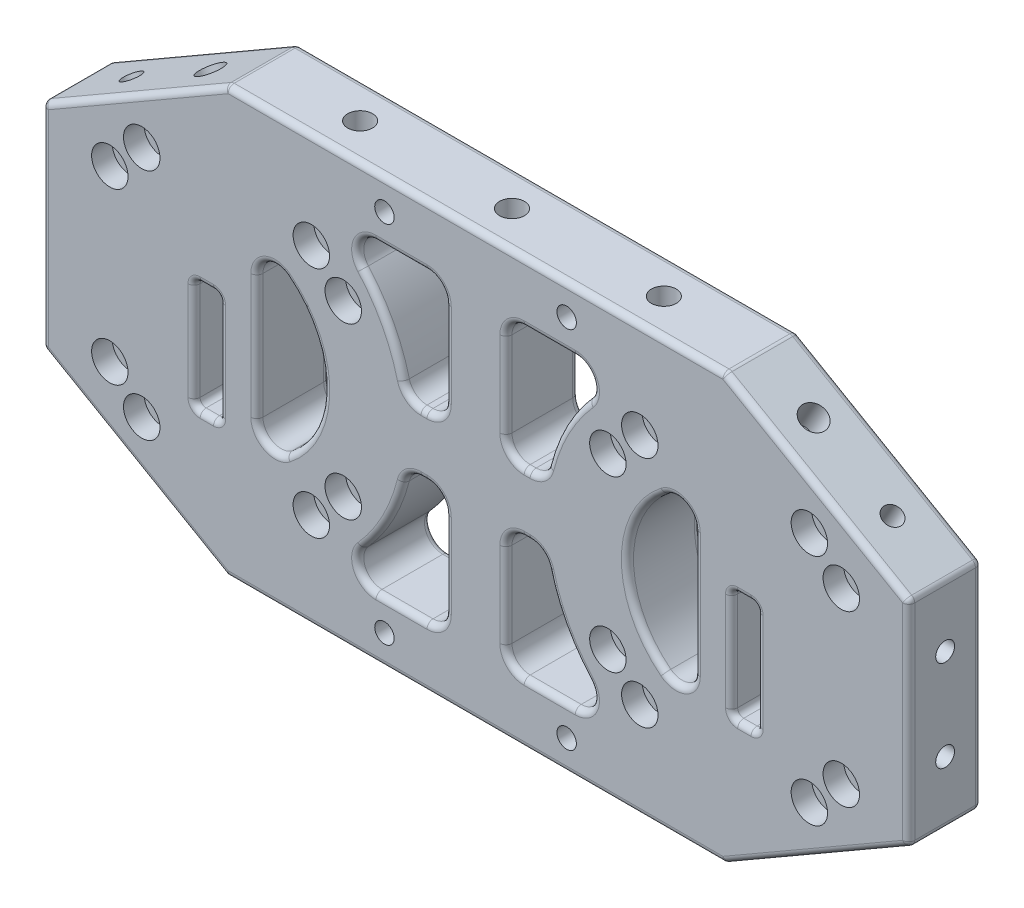
SolidWorks part; units mm, degrees
material "ABS"
ref_plane "前视基准面" through (0, 0, 0) normal (0, 0, 1) x (1, 0, 0)
ref_plane "上视基准面" through (0, 0, 0) normal (0, 1, 0) x (1, 0, 0)
ref_plane "右视基准面" through (0, 0, 0) normal (1, 0, 0) x (0, 0, -1)
other "Configuration Table"
sketch "草图1" plane through (0, 0, 0) normal (0, 0, 1) x (1, 0, 0)
  line L0 (0, 0) -> (41, 0)
  line L1 (0, 0) -> (41, 0) construction
  line L2 (0, 0) -> (0, 70) construction
  line L3 (0, 70) -> (41, 70) construction
  line L4 (41, 0) -> (41, 70) construction
  line L5 (0, 70) -> (41, 70)
  line L6 (-30.3109, 35) -> (41, 35) construction
  line L7 (0, 35) -> (-19.2142, 21.0401) construction
  line L8 (0, 35) -> (-13.9599, 15.7858) construction
  line L9 (41, 70) -> (41, 0)
  line L10 (0, 70) -> (-30.3109, 52.5)
  line L11 (0, 70) -> (-30.3109, 52.5) construction
  line L12 (-30.3109, 52.5) -> (-30.3109, 17.5) construction
  line L13 (-30.3109, 17.5) -> (0, 0) construction
  line L14 (36, 40) -> (36, 60)
  line L20 (36, 60) -> (16.5831, 60)
  line L21 (36, 40) -> (29.5804, 40)
  line L22 (36, 30) -> (36, 10)
  line L23 (36, 10) -> (16.5831, 10)
  line L24 (36, 30) -> (29.5804, 30)
  line L25 (0, 0) -> (30.3109, 17.5) construction
  line L26 (30.3109, 17.5) -> (30.3109, 52.5) construction
  line L27 (30.3109, 52.5) -> (0, 70) construction
  line L28 (-30.3109, 52.5) -> (-30.3109, 17.5)
  line L29 (-30.3109, 17.5) -> (0, 0)
  line L30 (5, 50.1987) -> (5, 19.8013)
  line L31 (-5.35, 39.6) -> (-1.15, 39.6)
  line L32 (-5.35, 39.6) -> (-5.35, 21.4)
  line L33 (-5.35, 21.4) -> (-1.15, 21.4)
  line L34 (-1.15, 39.6) -> (-1.15, 21.4)
  circle A2 centre (0, 35) radius 16 construction
  circle A4 centre (0, 35) radius 23.75 construction
  circle A14 centre (0, 35) radius 30 construction
  arc A24 (16.5831, 60) -> (29.5804, 40) centre (0, 35) cw
  arc A25 (16.5831, 10) -> (29.5804, 30) centre (0, 35) ccw
  circle A26 centre (0, 35) radius 30.3109 construction
  arc A27 (5, 50.1987) -> (5, 19.8013) centre (0, 35) cw
  point P13 (-19.2142, 21.0401)
  point P14 (-13.9599, 15.7858)
  point P23 (-13.9599, 54.2142)
  point P24 (-19.2142, 48.9599)
  point P25 (19.2142, 48.9599)
  point P26 (13.9599, 54.2142)
  point P27 (13.9599, 15.7858)
  point P28 (19.2142, 21.0401)
  dimension "D3" = 32
  dimension "D4" = 60
  dimension "D5" = 21.4
  dimension "D6" = 47.5
  dimension "D7" = 36
  dimension "D8" = 36
  dimension "D12" = 18.2
  dimension "D18" = 5
  dimension "D1" = 70
  dimension "D2" = 41
  dimension "D9" = 4
  dimension "D13" = 42.15
  dimension "D14" = 46.35
  dimension "D17" = 5
  dimension "D19" = 10
  dimension "D15" = 5
extrude "凸台-拉伸1" add sketch "草图1" along normal blind 12
mirror "镜向2" about plane through (41, 70, 12) normal (-1, 0, 0) of "凸台-拉伸1"
fillet "圆角2" radius 3 20 edges at (36, 30, 6) (36, 10, 6) (16.5831, 10, 6) (29.5804, 30, 6) (65.4169, 10, 6) (52.4196, 30, 6) (46, 30, 6) (46, 10, 6) (46, 40, 6) (46, 60, 6) (65.4169, 60, 6) (52.4196, 40, 6) (29.5804, 40, 6) (16.5831, 60, 6) (36, 40, 6) (36, 60, 6) (77, 50.1987, 6) (77, 19.8013, 6) (5, 50.1987, 6) (5, 19.8013, 6)
sketch "草图2" plane through (-30.3109, 52.5, 0) normal (-0.5, 0.866, 0) x (0.866, 0.5, 0)
  line L0 (0, -6) -> (35, -6) construction
  line L1 (0, -12) -> (0, 0) construction
  line L2 (35, -12) -> (35, 0) construction
  circle A0 centre (10, -6) radius 1.55
  circle A1 centre (25, -6) radius 1.55
  dimension "D1" = 3.1
  dimension "D2" = 3.1
  dimension "D3" = 15
  dimension "D4" = 10
extrude "切除-拉伸1" cut sketch "草图2" against normal blind 5
sketch "草图3" plane through (50.8109, 88.007, 0) normal (0.5, 0.866, 0) x (0.866, -0.5, 0)
  line L0 (36.0141, -6) -> (71.0141, -6) construction
  line L1 (36.0141, -12) -> (36.0141, 0) construction
  line L2 (71.0141, -12) -> (71.0141, 0) construction
  circle A0 centre (61.0141, -6) radius 1.55
  circle A1 centre (46.0141, -6) radius 1.55
  dimension "D1" = 3.1
  dimension "D2" = 3.1
  dimension "D3" = 15
  dimension "D4" = 10
extrude "切除-拉伸2" cut sketch "草图3" against normal blind 5
sketch "草图4" plane through (0, 0, 0) normal (-0.5, -0.866, 0) x (0.866, -0.5, 0)
  line L0 (-35, 6) -> (0, 6) construction
  line L1 (-35, 12) -> (-35, 0) construction
  line L2 (0, 12) -> (0, 0) construction
  circle A0 centre (-10, 6) radius 1.55
  circle A1 centre (-25, 6) radius 1.55
  dimension "D3" = 3.1
  dimension "D4" = 3.1
  dimension "D1" = 15
  dimension "D2" = 10
extrude "切除-拉伸3" cut sketch "草图4" against normal blind 5
sketch "草图5" plane through (20.5, -35.507, 0) normal (0.5, -0.866, 0) x (0.866, 0.5, 0)
  line L0 (71.0141, 6) -> (106.0141, 6) construction
  line L1 (71.0141, 12) -> (71.0141, 0) construction
  line L2 (106.0141, 12) -> (106.0141, 0) construction
  circle A0 centre (81.0141, 6) radius 1.55
  circle A1 centre (96.0141, 6) radius 1.55
  dimension "D1" = 3.1
  dimension "D2" = 3.1
  dimension "D3" = 15
  dimension "D4" = 10
extrude "切除-拉伸4" cut sketch "草图5" against normal blind 5
sketch "草图6" plane through (112.3109, 0, 0) normal (1, 0, 0) x (0, 0, -1)
  line L0 (-6, 52.5) -> (-6, 17.5) construction
  line L1 (-12, 52.5) -> (0, 52.5) construction
  line L2 (-12, 17.5) -> (0, 17.5) construction
  circle A0 centre (-6, 42.5) radius 1.55
  circle A1 centre (-6, 27.5) radius 1.55
  dimension "D1" = 3.1
  dimension "D2" = 3.1
  dimension "D3" = 15
  dimension "D4" = 10
extrude "切除-拉伸5" cut sketch "草图6" against normal blind 5
sketch "草图7" plane through (0, 0, 0) normal (0, -1, 0) x (1, 0, 0)
  line L0 (0, 6) -> (82, 6) construction
  line L1 (0, 12) -> (0, 0) construction
  line L2 (82, 12) -> (82, 0) construction
  circle A0 centre (16, 6) radius 2.05
  circle A1 centre (41, 6) radius 2.05
  circle A2 centre (66, 6) radius 2.05
  dimension "D1" = 4.1
  dimension "D2" = 4.1
  dimension "D3" = 4.1
  dimension "D4" = 25
  dimension "D5" = 25
extrude "切除-拉伸6" cut sketch "草图7" against normal blind 5
sketch "草图8" plane through (0, 70, 0) normal (0, 1, 0) x (1, 0, 0)
  line L0 (0, -6) -> (82, -6) construction
  line L1 (0, -12) -> (0, 0) construction
  line L2 (82, -12) -> (82, 0) construction
  circle A0 centre (41, -6) radius 2.05
  circle A1 centre (66, -6) radius 2.05
  circle A2 centre (16, -6) radius 2.05
  dimension "D3" = 4.1
  dimension "D4" = 4.1
  dimension "D5" = 4.1
  dimension "D1" = 25
  dimension "D2" = 25
extrude "切除-拉伸7" cut sketch "草图8" against normal blind 5
sketch "草图9" plane through (-30.3109, 0, 0) normal (-1, 0, 0) x (0, 0, 1)
  line L0 (6, 52.5) -> (6, 17.5) construction
  line L1 (12, 52.5) -> (0, 52.5) construction
  line L2 (12, 17.5) -> (0, 17.5) construction
  circle A0 centre (6, 42.5) radius 1.55
  circle A1 centre (6, 27.5) radius 1.55
  dimension "D3" = 3.1
  dimension "D4" = 3.1
  dimension "D1" = 15
  dimension "D2" = 10
extrude "切除-拉伸8" cut sketch "草图9" against normal blind 5
sketch "草图10" plane through (-30.3109, 52.5, 0) normal (-0.5, 0.866, 0) x (0.866, 0.5, 0)
  circle A0 centre (25, -6) radius 2.05
  dimension "D1" = 4.1
extrude "切除-拉伸9" cut sketch "草图10" against normal blind 5
sketch "草图11" plane through (50.8109, 88.007, 0) normal (0.5, 0.866, 0) x (0.866, -0.5, 0)
  circle A0 centre (46.0141, -6) radius 2.05
  dimension "D1" = 4.1
extrude "切除-拉伸10" cut sketch "草图11" against normal blind 5
fillet "圆角3" radius 1 128 edges at (-3.25, 39.6, 12) (-3.25, 39.6, 0) (-3.25, 21.4, 12) (-3.25, 21.4, 0) (85.25, 39.6, 0) (85.25, 39.6, 12) (85.25, 21.4, 0) (85.25, 21.4, 12) (6.6844, 47.9431, 0) (16, 35, 0) (6.6844, 22.0569, 0) (6.6844, 47.9431, 12) (16, 35, 12) (6.6844, 22.0569, 12) (75.3156, 47.9431, 12) (66, 35, 12) (66, 35, 0) (75.3156, 22.0569, 12) (75.3156, 47.9431, 0) (75.3156, 22.0569, 0) (51.8308, 29.3645, 12) (49.4922, 30, 0) (49.4922, 30, 12) (46.8787, 29.1213, 12) (46, 20, 0) (46, 20, 12) (46.8787, 10.8787, 12) (53.2016, 10, 12) (53.2016, 10, 0) (60.1419, 11.7753, 12) (51.8308, 29.3645, 0) (46.8787, 29.1213, 0) (46.8787, 10.8787, 0) (60.1419, 11.7753, 0) (60.1419, 58.2247, 0) (53.2016, 60, 12) (53.2016, 60, 0) (46.8787, 59.1213, 0) (46, 50, 12) (46, 50, 0) (46.8787, 40.8787, 0) (49.4922, 40, 0) (49.4922, 40, 12) (51.8308, 40.6355, 0) (60.1419, 58.2247, 12) (46.8787, 59.1213, 12) (46.8787, 40.8787, 12) (51.8308, 40.6355, 12) (21.8581, 58.2247, 0) (28.7984, 60, 0) (35.1213, 59.1213, 0) (36, 50, 0) (35.1213, 40.8787, 0) (32.5078, 40, 0) (30.1692, 40.6355, 0) (21.8581, 58.2247, 12) (28.7984, 60, 12) (35.1213, 59.1213, 12) (36, 50, 12) (35.1213, 40.8787, 12) (32.5078, 40, 12) (30.1692, 40.6355, 12) (30.1692, 29.3645, 0) (32.5078, 30, 0) (35.1213, 29.1213, 0) (36, 20, 0) (35.1213, 10.8787, 0) (28.7984, 10, 0) (21.8581, 11.7753, 0) (30.1692, 29.3645, 12) (32.5078, 30, 12) (35.1213, 29.1213, 12) (36, 20, 12) (35.1213, 10.8787, 12) (28.7984, 10, 12) (21.8581, 11.7753, 12) (-5.35, 21.4, 6) (-5.35, 30.5, 12) (-5.35, 39.6, 6) (-5.35, 30.5, 0) (-1.15, 39.6, 6) (-1.15, 30.5, 12) (-1.15, 21.4, 6) (-1.15, 30.5, 0) (83.15, 21.4, 6) (83.15, 30.5, 0) (83.15, 30.5, 12) (83.15, 39.6, 6) (87.35, 39.6, 6) (87.35, 30.5, 0) (87.35, 30.5, 12) (87.35, 21.4, 6) (5, 35, 0) (5, 35, 12) (77, 35, 0) (77, 35, 12) (55.4919, 20.9529, 0) (55.4919, 20.9529, 12) (55.4919, 49.0471, 12) (55.4919, 49.0471, 0) (26.5081, 49.0471, 0) (26.5081, 49.0471, 12) (26.5081, 20.9529, 0) (26.5081, 20.9529, 12) (41, 70, 12) (97.1554, 61.25, 0) (97.1554, 61.25, 12) (112.3109, 35, 0) (112.3109, 35, 12) (97.1554, 8.75, 0) (97.1554, 8.75, 12) (41, 0, 12) (-15.1554, 8.75, 12) (-15.1554, 61.25, 12) (-30.3109, 35, 12) (-15.1554, 8.75, 0) (-30.3109, 35, 0) (-15.1554, 61.25, 0) (41, 70, 0) (41, 0, 0) (0, 70, 6) (-30.3109, 52.5, 6) (-30.3109, 17.5, 6) (0, 0, 6) (112.3109, 17.5, 6) (82, 0, 6) (112.3109, 52.5, 6) (82, 70, 6)
sketch "草图12" plane through (0, 0, 12) normal (0, 0, 1) x (1, 0, 0)
  line L0 (41, 70) -> (41, 0) construction
  line L1 (0.2679, 70) -> (81.7321, 70) construction
  line L2 (81.7321, 0) -> (0.2679, 0) construction
  line L3 (0, 35) -> (0, 11.25) construction
  line L4 (0, 35) -> (-23.75, 35) construction
  line L5 (-19.2142, 21.0401) -> (0, 35) construction
  line L6 (0, 35) -> (-13.9599, 15.7858) construction
  circle A0 centre (0, 35) radius 23.75 construction
  point P10 (-19.2142, 21.0401)
  point P13 (-13.9599, 15.7858)
  point P15 (62.7858, 21.0401)
  point P17 (68.0401, 15.7858)
  point P18 (95.9599, 15.7858)
  point P19 (-13.9599, 54.2142)
  point P20 (-19.2142, 48.9599)
  point P21 (19.2142, 48.9599)
  point P22 (13.9599, 54.2142)
  point P23 (13.9599, 15.7858)
  point P24 (19.2142, 21.0401)
  point P25 (101.2142, 21.0401)
  point P26 (101.2142, 48.9599)
  point P27 (95.9599, 54.2142)
  point P28 (68.0401, 54.2142)
  point P29 (62.7858, 48.9599)
  dimension "D1" = 47.5
  dimension "D2" = 36
  dimension "D3" = 36
  dimension "D4" = 4
hole_wizard "M3 六角圆柱头螺钉的柱形沉头孔1" positions "草图12" profile "草图13" counterbore size "M3" standard "GB" end condition through all
sketch "草图13" plane through (62.7858, 48.9599, 12) normal (1, 0, 0) x (0, -1, 0)
  line L0 (0, 0) -> (0, 12)
  line L1 (0, 12) -> (1.6, 12)
  line L3 (1.6, 12) -> (1.6, 3.4)
  line L4 (1.6, 3.4) -> (3, 3.4)
  line L5 (3, 3.4) -> (3, 0)
  line L7 (3, 0) -> (0, 0)
  line L11 (0, -6.35) -> (0, 107.95) construction
  dimension "通孔孔直径" = 3.2
  dimension "通孔孔深度" = 12
  dimension "柱形沉头孔直径" = 6
  dimension "柱形沉头孔深度" = 3.4
sketch "草图14" plane through (0, 0, 0) normal (0, 0, -1) x (-1, 0, 0)
  line L0 (-41, 70) -> (-41, 0) construction
  line L1 (-81.7321, 70) -> (-0.2679, 70) construction
  line L2 (-0.2679, 0) -> (-81.7321, 0) construction
  point P6 (-56, 65)
  point P7 (-56, 5)
  point P8 (-26, 5)
  point P9 (-26, 65)
  dimension "D1" = 15
  dimension "D2" = 15
  dimension "D3" = 5
  dimension "D4" = 5
hole_wizard "M3 六角圆柱头螺钉的柱形沉头孔2" positions "草图14" profile "草图15" counterbore size "M3" standard "GB" end condition through all
sketch "草图15" plane through (26, 65, 0) normal (1, 0, 0) x (0, 1, 0)
  line L0 (0, 0) -> (0, 12)
  line L1 (0, 12) -> (1.6, 12)
  line L3 (1.6, 12) -> (1.6, 3.4)
  line L4 (1.6, 3.4) -> (3, 3.4)
  line L5 (3, 3.4) -> (3, 0)
  line L7 (3, 0) -> (0, 0)
  line L11 (0, -6.35) -> (0, 107.95) construction
  dimension "通孔孔直径" = 3.2
  dimension "通孔孔深度" = 12
  dimension "柱形沉头孔直径" = 6
  dimension "柱形沉头孔深度" = 3.4
